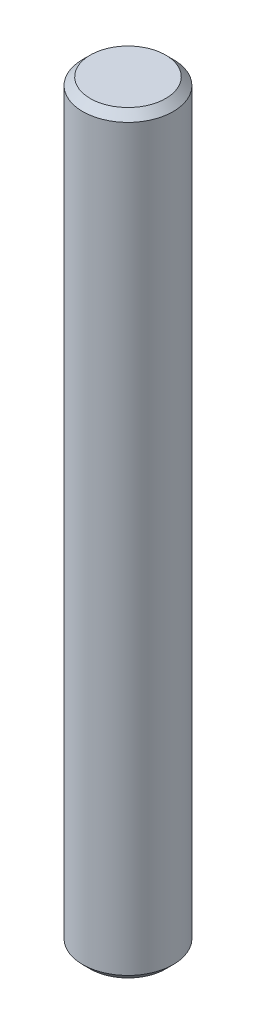
SolidWorks part; units mm, degrees
ref_plane "Front Plane" through (0, 0, 0) normal (0, 0, 1) x (1, 0, 0)
ref_plane "Top Plane" through (0, 0, 0) normal (0, 1, 0) x (1, 0, 0)
ref_plane "Right Plane" through (0, 0, 0) normal (1, 0, 0) x (0, 0, -1)
sketch "Sketch1" plane through (0, 0, 0) normal (0, 1, 0) x (1, 0, 0)
  circle A0 centre (0, 0) radius 1.5
  dimension "D1" = 3
extrude "Boss-Extrude1" add sketch "Sketch1" along normal blind 25
chamfer "Chamfer1" distance 0.25 angle 45 2 edges at (0, 0, 1.5) (0, 25, 1.5)
